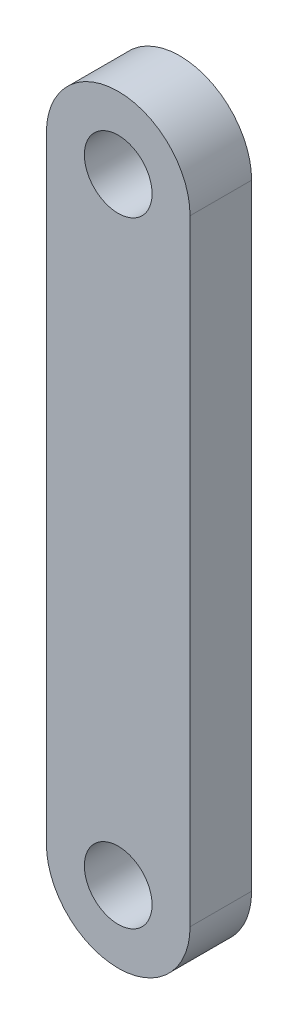
SolidWorks part; units mm, degrees
ref_plane "前视基准面" through (0, 0, 0) normal (0, 0, 1) x (1, 0, 0)
ref_plane "上视基准面" through (0, 0, 0) normal (0, 1, 0) x (1, 0, 0)
ref_plane "右视基准面" through (0, 0, 0) normal (1, 0, 0) x (0, 0, -1)
other "Configuration Table"
sketch "草图1" plane through (0, 0, 0) normal (0, 0, 1) x (1, 0, 0)
  line L0 (0, 15) -> (0, -15) construction
  line L1 (3.5, 15) -> (3.5, -15)
  line L2 (-3.5, 15) -> (-3.5, -15)
  arc A0 (3.5, 15) -> (-3.5, 15) centre (0, 15) ccw
  arc A1 (-3.5, -15) -> (3.5, -15) centre (0, -15) ccw
  circle A2 centre (0, 15) radius 1.65
  circle A3 centre (0, -15) radius 1.65
  point P2 (0, 0)
  dimension "D1" = 3.5
  dimension "D2" = 30
  dimension "D3" = 3.3
extrude "凸台-拉伸1" add sketch "草图1" along normal blind 3
